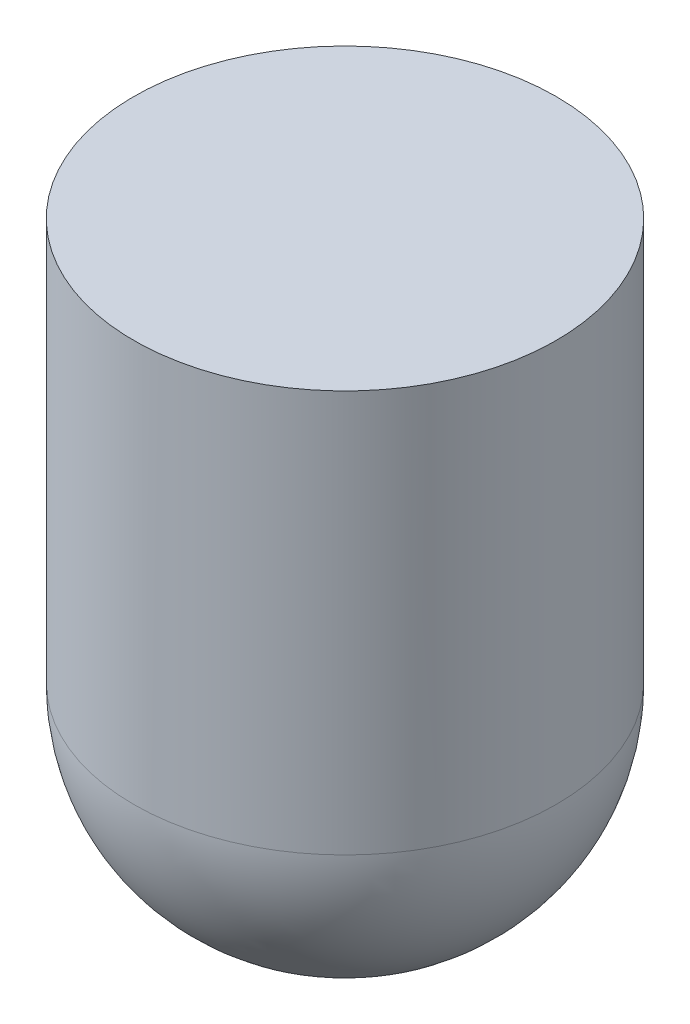
SolidWorks part; units mm, degrees
ref_plane "Front Plane" through (0, 0, 0) normal (0, 0, 1) x (1, 0, 0)
ref_plane "Top Plane" through (0, 0, 0) normal (0, 1, 0) x (1, 0, 0)
ref_plane "Right Plane" through (0, 0, 0) normal (1, 0, 0) x (0, 0, -1)
sketch "Sketch2" plane through (0, 0, 0) normal (0, 1, 0) x (1, 0, 0)
  circle A0 centre (0, 0) radius 130.175
extrude "Boss-Extrude1" add sketch "Sketch2" along normal blind 374.65
fillet "Fillet1" radius 127 1 edges at (0, 0, 130.175)
